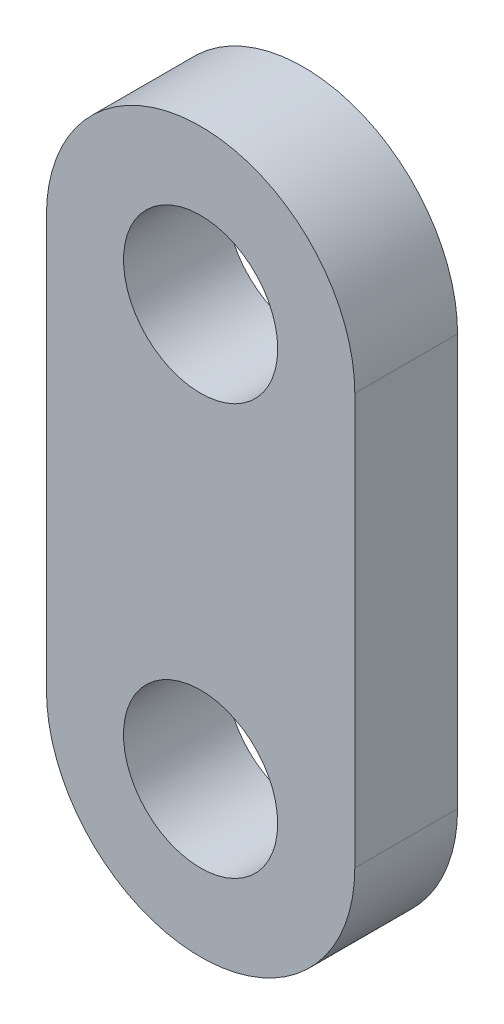
SolidWorks part; units mm, degrees
ref_plane "Front Plane" through (0, 0, 0) normal (0, 0, 1) x (1, 0, 0)
ref_plane "Top Plane" through (0, 0, 0) normal (0, 1, 0) x (1, 0, 0)
ref_plane "Right Plane" through (0, 0, 0) normal (1, 0, 0) x (0, 0, -1)
sketch "Sketch1" plane through (0, 0, 0) normal (0, 0, 1) x (1, 0, 0)
  line L0 (-4.7625, 0) -> (-4.7625, 12.7)
  line L1 (4.7625, 12.7) -> (4.7625, 0)
  circle A0 centre (0, 0) radius 4.7625
  circle A1 centre (0, 0) radius 2.3813
  circle A2 centre (0, 12.7) radius 2.3813
  circle A3 centre (0, 12.7) radius 4.7625
  dimension "D1" = 9.525
  dimension "D2" = 4.7625
  dimension "D3" = 4.7625
  dimension "D4" = 12.7
  dimension "D5" = 9.525
extrude "Boss-Extrude1" add sketch "Sketch1" along normal blind 3.175 contours A3 L0 A0 L1 | A3 A2 | A0 A1
